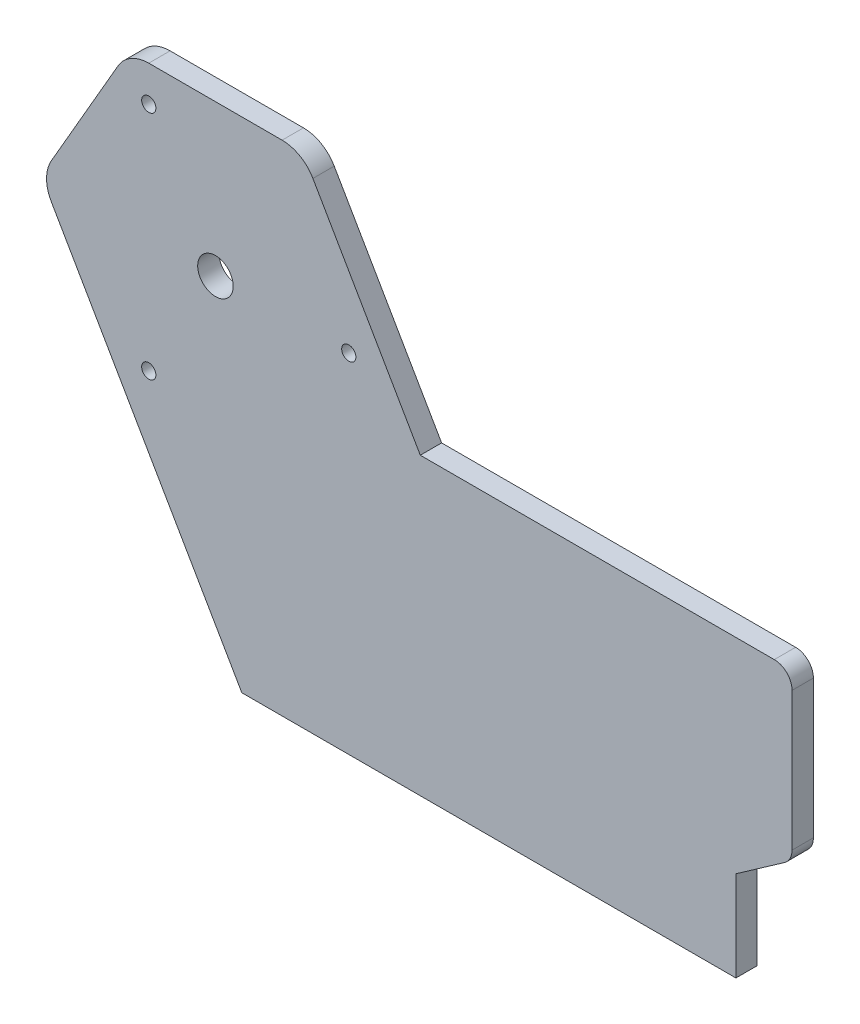
SolidWorks part; units mm, degrees
ref_plane "Front Plane" through (0, 0, 0) normal (0, 0, 1) x (1, 0, 0)
ref_plane "Top Plane" through (0, 0, 0) normal (0, 1, 0) x (1, 0, 0)
ref_plane "Right Plane" through (0, 0, 0) normal (1, 0, 0) x (0, 0, -1)
sketch "Sketch1" plane through (0, 0, 0) normal (0, 0, 1) x (1, 0, 0)
  line L9 (-122.6526, 114.8455) -> (-69.0483, 22)
  line L10 (-69.0483, 22) -> (70, 22)
  line L11 (70, 22) -> (70, 47.4)
  line L12 (70, 47.4) -> (83.6679, 56.9704)
  line L13 (85.8, 61.0661) -> (85.8, 100)
  line L14 (80.8, 105) -> (-18.8188, 105)
  line L15 (-18.8188, 105) -> (-49.0405, 157.3455)
  line L16 (-57.7007, 162.3455) -> (-95.2285, 162.3455)
  line L17 (-103.8888, 157.3455) -> (-122.6526, 124.8455)
  circle A9 centre (-95.2285, 87.3455) radius 2
  circle A10 centre (-38.9369, 119.8455) radius 2
  circle A11 centre (-76.4646, 119.8455) radius 5
  circle A12 centre (-95.2285, 152.3455) radius 2
  arc A13 (-122.6526, 124.8455) -> (-122.6526, 114.8455) centre (-113.9924, 119.8455) ccw
  arc A14 (83.6679, 56.9704) -> (85.8, 61.0661) centre (80.8, 61.0661) ccw
  arc A15 (85.8, 100) -> (80.8, 105) centre (80.8, 100) ccw
  arc A16 (-49.0405, 157.3455) -> (-57.7007, 162.3455) centre (-57.7007, 152.3455) ccw
  arc A17 (-95.2285, 162.3455) -> (-103.8888, 157.3455) centre (-95.2285, 152.3455) ccw
  point P1 (0, 0)
  point P3 (0, 0)
  point P5 (0, 0)
  point P7 (0, 0)
  point P20 (0, 0)
  point P22 (0, 0)
  point P25 (0, 0)
  dimension "D4" = 5
  dimension "D16" = 10
  dimension "D18" = 4
  dimension "D19" = 10
  dimension "D1" = 99.6188
  dimension "D2" = 60.4434
  dimension "D3" = 139.0483
  dimension "D5" = 90
  dimension "D6" = 38.9339
  dimension "D7" = 16.6854
  dimension "D8" = 25.4
  dimension "D9" = 37.5278
  dimension "D10" = 60
  dimension "D11" = 60
  dimension "D12" = 120
  dimension "D13" = 22
  dimension "D14" = 70
  dimension "D15" = 125
  dimension "D17" = 60
  dimension "D20" = 65
  dimension "D21" = 65
  dimension "D22" = 65
  dimension "D23" = 10
  dimension "D24" = 42.5
  dimension "D25" = 37.5278
  dimension "D26" = 37.5278
extrude "Boss-Extrude1" add sketch "Sketch1" along normal blind 6 separate body
